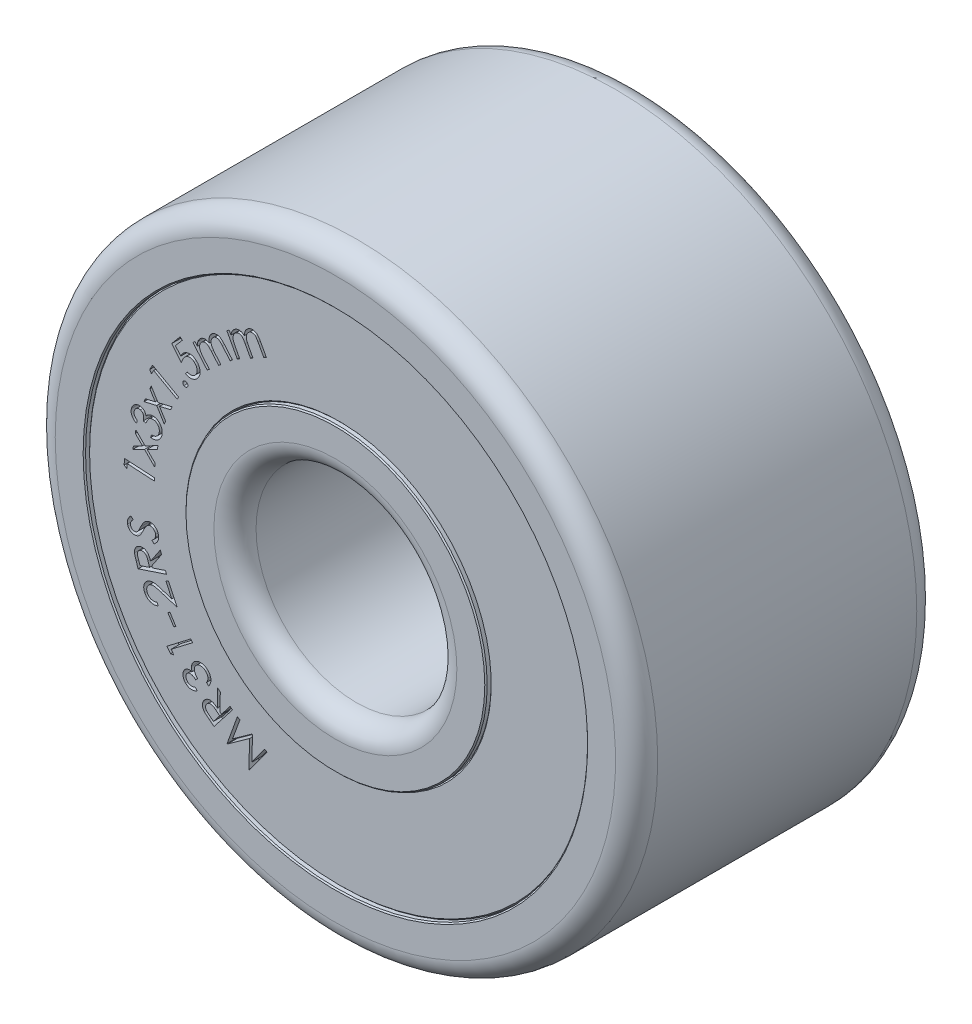
SolidWorks part; units mm, degrees
material "AISI 316 Annealed Stainless Steel Bar (SS)"
ref_plane "Front" through (0, 0, 0) normal (0, 0, 1) x (1, 0, 0)
ref_plane "Top" through (0, 0, 0) normal (0, 1, 0) x (1, 0, 0)
ref_plane "Right" through (0, 0, 0) normal (1, 0, 0) x (0, 0, -1)
sketch "LAYOUT R" plane through (0, 0, 0) normal (1, 0, 0) x (0, 0, -1)
  line L0 (-0.75, 0.5) -> (0.75, 0.5)
  line L1 (0.75, -1.5) -> (-0.75, -1.5) construction
  line L2 (0.75, -1.5) -> (0.75, 1.5) construction
  line L3 (0.75, 1.5) -> (-0.75, 1.5)
  line L4 (-0.75, -1.5) -> (-0.75, 1.5) construction
  line L5 (0.75, -1.5) -> (-0.75, 1.5) construction
  line L6 (0.75, 1.5) -> (-0.75, -1.5) construction
  line L7 (-0.75, 0.75) -> (0.75, 0.75)
  line L8 (-0.75, 1.25) -> (0.75, 1.25)
  line L11 (-17.5, 0) -> (17.5, 0) construction
  line L12 (-0.75, 1.5) -> (-0.75, 1.25)
  line L13 (0.75, 1.5) -> (0.75, 1.25)
  line L14 (-0.75, 1.25) -> (-0.75, 0.75)
  line L15 (0.75, 1.25) -> (0.75, 0.75)
  line L16 (-0.75, 0.75) -> (-0.75, 0.5)
  line L17 (0.75, 0.75) -> (0.75, 0.5)
  line L18 (-0.73, 1.25) -> (-0.73, 0.75)
  line L19 (0.73, 1.25) -> (0.73, 0.75)
  point P0 (0, 0)
  point P15 (0, 0)
  dimension "D1" = 1.5
  dimension "D2" = 3
  dimension "D3" = 0.5
  dimension "D6" = 0.02
  dimension "D7" = 0.02
  dimension "D4" = 0.75
  dimension "D5" = 1.25
sketch "Sketch R, INNER BODY" plane through (0, 0, 0) normal (1, 0, 0) x (0, 0, -1)
  line L0 (-0.75, 0.5) -> (0.75, 0.5) construction
  line L2 (-0.75, 0.75) -> (0.75, 0.75) construction
  line L4 (-0.75, 0.5) -> (0.75, 0.5)
  line L6 (-0.75, 0.75) -> (0.75, 0.75)
  line L8 (0.75, 0.75) -> (0.75, 0.5) construction
  line L9 (-0.75, 0.75) -> (-0.75, 0.5) construction
  line L10 (0.75, 0.75) -> (0.75, 0.5)
  line L11 (-0.75, 0.75) -> (-0.75, 0.5)
  line L12 (-17.5, 0) -> (17.5, 0) construction
  line L13 (-17.5, 0) -> (17.5, 0) construction
sketch "Sketch R, OUTER BODY" plane through (0, 0, 0) normal (1, 0, 0) x (0, 0, -1)
  line L2 (-0.75, 1.25) -> (0.75, 1.25) construction
  line L3 (0.75, 1.5) -> (-0.75, 1.5) construction
  line L6 (-0.75, 1.25) -> (0.75, 1.25)
  line L7 (0.75, 1.5) -> (-0.75, 1.5)
  line L8 (-17.5, 0) -> (17.5, 0) construction
  line L9 (-17.5, 0) -> (17.5, 0) construction
  line L10 (0.75, 1.5) -> (0.75, 1.25) construction
  line L11 (-0.75, 1.5) -> (-0.75, 1.25) construction
  line L12 (0.75, 1.5) -> (0.75, 1.25)
  line L13 (-0.75, 1.5) -> (-0.75, 1.25)
sketch "Sketch R, SEAL FACES" plane through (0, 0, 0) normal (1, 0, 0) x (0, 0, -1)
  line L0 (-17.5, 0) -> (17.5, 0) construction
  line L1 (-17.5, 0) -> (17.5, 0) construction
  line L3 (-0.75, 0.75) -> (0.75, 0.75) construction
  line L5 (-0.75, 1.25) -> (0.75, 1.25) construction
  line L7 (-0.73, 0.75) -> (0.73, 0.75)
  line L9 (-0.73, 1.25) -> (0.73, 1.25)
  line L10 (0.73, 1.25) -> (0.73, 0.75) construction
  line L11 (-0.73, 1.25) -> (-0.73, 0.75) construction
  line L12 (0.73, 1.25) -> (0.73, 0.75)
  line L13 (-0.73, 1.25) -> (-0.73, 0.75)
revolve "Revolve INNER BODY" add sketch "Sketch R, INNER BODY" angle 360 about L13
fillet "Fillet INNER BODY" radius 0.105 2 edges at (0.5, 0, 0.75) (0.5, 0, -0.75)
chamfer "Chamfer INNER BODY" distance 0.006 angle 45 2 edges at (0.75, 0, -0.75) (0.75, 0, 0.75)
revolve "Revolve OUTER BODY" add sketch "Sketch R, OUTER BODY" angle 360 about L9
fillet "Fillet OUTER BODY" radius 0.105 2 edges at (1.5, 0, -0.75) (1.5, 0, 0.75)
chamfer "Chamfer OUTER BODY" distance 0.006 angle 45 2 edges at (1.25, 0, 0.75) (1.25, 0, -0.75)
revolve "Revolve SEALS" add sketch "Sketch R, SEAL FACES" angle 360 about L1
chamfer "Chamfer SEALS" distance 0.006 angle 45 4 edges at (0.75, 0, -0.73) (1.25, 0, -0.73) (1.25, 0, 0.73) (0.75, 0, 0.73)
sketch "Sketch TEXT RADIUS 1 — MANUALLY ASSIGN TEXT AND FONT SIZE (FROM EQUATIONS)" plane through (0, 0, 0.73) normal (0, 0, 1) x (1, 0, 0)
  circle A0 centre (0, 0) radius 0.925 construction
  text T0 "MR31-2RS  1x3x1.5mm" font "Century Gothic" height 0.15
  dimension "D1" = 1.85
extrude "Cut-Extrude SEAL LABEL 1" cut sketch "Sketch TEXT RADIUS 1 — MANUALLY ASSIGN TEXT AND FONT SIZE (FROM EQUATIONS)" against normal blind 0.05
sketch "Sketch TEXT RADIUS 2 — MANUALLY ASSIGN TEXT AND FONT SIZE (FROM EQUATIONS)" plane through (0, 0, -0.73) normal (0, 0, -1) x (-1, 0, 0)
  circle A0 centre (0, 0) radius 0.925 construction
  text T0 "MR31-2RS  1x3x1.5mm" font "Century Gothic" height 0.15
  dimension "D1" = 1.85
extrude "Cut-Extrude SEAL LABEL 2" cut sketch "Sketch TEXT RADIUS 2 — MANUALLY ASSIGN TEXT AND FONT SIZE (FROM EQUATIONS)" against normal blind 0.05
equation "\"_i__BORE\"= 1"
equation "\"_i__OUTSIDE_DIAMETER\"= 3"
equation "\"_i__WIDTH\"= 1.5"
equation "\"_i_optional__TEXT_RADIUS_ADJUSTMENT\"= 0"
equation "\"_output__FONT_SIZE_mm\"= \"BODY_SPAN__SEAL__OF_RADIUS\" * \"param__FONT_SIZE_RATIO\"'MANUALLY ASSIGN TO FONT"
equation "\"BODY__HALF_WIDTH\"= \"_i__WIDTH\" / 2"
equation "\"BODY_SPAN___OF_DIAMETER\"= \"_i__OUTSIDE_DIAMETER\" - \"_i__BORE\""
equation "\"BODY_SPAN___OF_RADIUS\"= \"BODY_SPAN___OF_DIAMETER\" / 2"
equation "\"BODY_SPAN__BORE_AND_OD__OF RADIUS\"= ( \"BODY_SPAN___OF_RADIUS\" - \"BODY_SPAN__SEAL__OF_RADIUS\" ) / 2"
equation "\"BODY_SPAN__SEAL__OF_RADIUS\"= \"BODY_SPAN___OF_RADIUS\" * \"param__SEAL_PANEL_SPAN__RATIO_OF_BODY_RADIAN\""
equation "\"BORE__RADIUS\"= \"_i__BORE\" / 2"
equation "\"CORNER_RADII\"= \"_i__WIDTH\" * \"param__CORNER_RADII__ISO_MAX_RATIO_TO_WIDTH\""
equation "\"param__CORNER_RADII__ISO_MAX_RATIO_TO_WIDTH\"= 0.07'WHERE WIDTH IS LESS THAN DIAMETER"
equation "\"param__FONT_SIZE_RATIO\"= 0.3"
equation "\"param__SEAL_FACE_INSET__RATIO_OF_WIDTH\"= .01"
equation "\"param__SEAL_PANEL_SPAN__RATIO_OF_BODY_RADIAN\"= 0.5"
equation "\"param__SIDE_CHAMFERS__RATIO_TO_OD\"= 1 / 500"
equation "\"RING_INNER__OUTSIDE_RADIUS\"= \"BORE__RADIUS\" + \"BODY_SPAN__BORE_AND_OD__OF RADIUS\""
equation "\"RING_OUTER__OUTSIDE_RADIUS\"= ( \"_i__OUTSIDE_DIAMETER\" / 2 ) - \"BODY_SPAN__BORE_AND_OD__OF RADIUS\""
equation "\"SEAL_FACE_INSET\"= \"_i__WIDTH\" * \"param__SEAL_FACE_INSET__RATIO_OF_WIDTH\""
equation "\"SIDE_FACE_AND_SEAL_CHAMFERS\"= \"_i__OUTSIDE_DIAMETER\" * \"param__SIDE_CHAMFERS__RATIO_TO_OD\""
equation "\"TEXT_RADIUS\"= \"_i__BORE\" + ( \"BODY_SPAN___OF_DIAMETER\" / 2 ) - \"_output__FONT_SIZE_mm\" + \"_i_optional__TEXT_RADIUS_ADJUSTMENT\""
equation "\"D1@Chamfer INNER BODY\"=\"SIDE_FACE_AND_SEAL_CHAMFERS\""
equation "\"D1@Chamfer OUTER BODY\"=\"SIDE_FACE_AND_SEAL_CHAMFERS\""
equation "\"D1@Chamfer SEALS\"=\"SIDE_FACE_AND_SEAL_CHAMFERS\""
equation "\"D1@Fillet INNER BODY\"=\"CORNER_RADII\""
equation "\"D1@Fillet OUTER BODY\"=\"CORNER_RADII\""
equation "\"D1@LAYOUT R\"=\"_i__WIDTH\""
equation "\"D1@Sketch TEXT RADIUS 1 — MANUALLY ASSIGN TEXT AND FONT SIZE (FROM EQUATIONS)\" = \"TEXT_RADIUS\""
equation "\"D1@Sketch TEXT RADIUS 2 — MANUALLY ASSIGN TEXT AND FONT SIZE (FROM EQUATIONS)\" = \"TEXT_RADIUS\""
equation "\"D2@LAYOUT R\"=\"_i__OUTSIDE_DIAMETER\""
equation "\"D3@LAYOUT R\"=\"BORE__RADIUS\""
equation "\"D4@LAYOUT R\"=\"RING_INNER__OUTSIDE_RADIUS\""
equation "\"D5@LAYOUT R\"=\"RING_OUTER__OUTSIDE_RADIUS\""
